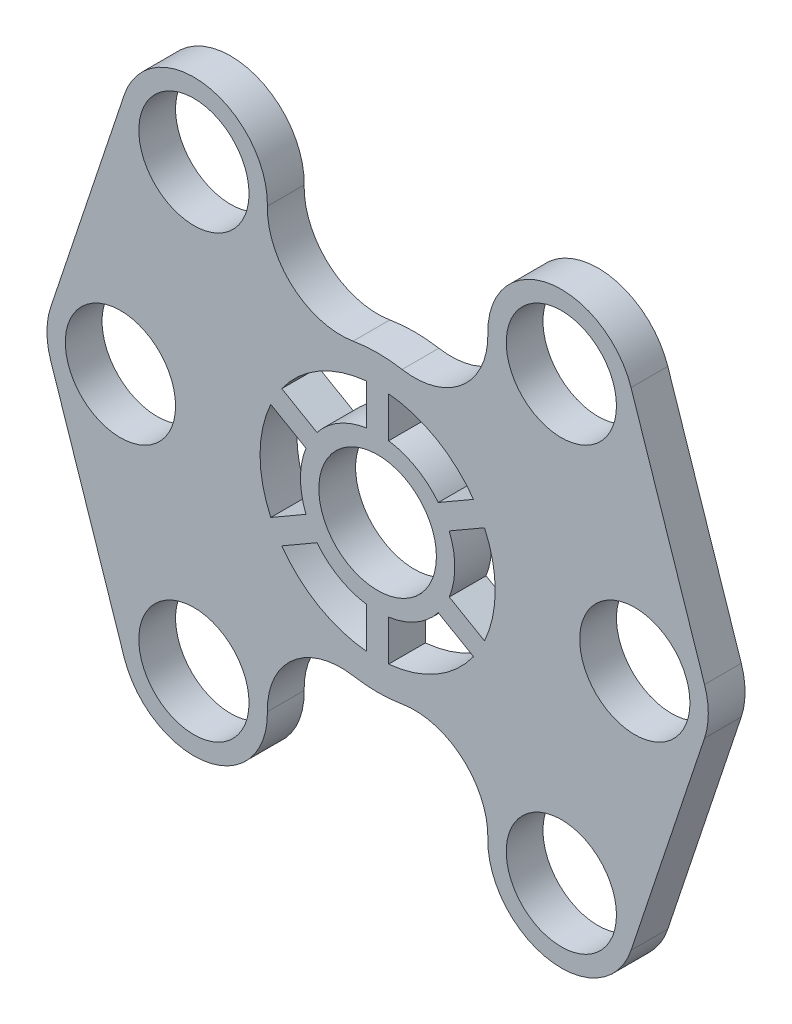
SolidWorks part; units mm, degrees
ref_plane "Front Plane" through (0, 0, 0) normal (0, 0, 1) x (1, 0, 0)
ref_plane "Top Plane" through (0, 0, 0) normal (0, 1, 0) x (1, 0, 0)
ref_plane "Right Plane" through (0, 0, 0) normal (1, 0, 0) x (0, 0, -1)
sketch "Sketch1" plane through (0, 0, 0) normal (0, 0, 1) x (1, 0, 0)
  line L0 (0, -30.4712) -> (0, 30.4712) construction
  line L1 (0, 0) -> (51.2653, 0) construction
  line L2 (-3, -20.7846) -> (-3, -31.8591)
  line L3 (3, -20.7846) -> (3, -31.8591)
  line L4 (-19.5, -7.7942) -> (-29.0908, -13.3315)
  line L5 (-16.5, -12.9904) -> (-26.0908, -18.5276)
  line L6 (-16.5, 12.9904) -> (-26.0908, 18.5276)
  line L7 (-19.5, 7.7942) -> (-29.0908, 13.3315)
  line L8 (3, 20.7846) -> (3, 31.8591)
  line L9 (-3, 20.7846) -> (-3, 31.8591)
  line L10 (19.5, 7.7942) -> (29.0908, 13.3315)
  line L11 (16.5, 12.9904) -> (26.0908, 18.5276)
  line L12 (16.5, -12.9904) -> (26.0908, -18.5276)
  line L13 (19.5, -7.7942) -> (29.0908, -13.3315)
  line L14 (68.9737, 66.3246) -> (88.9737, 6.3246)
  line L15 (68.9737, -66.3246) -> (88.9737, -6.3246)
  line L16 (0, 0) -> (-51.2653, 0) construction
  line L17 (-68.9737, -66.3246) -> (-88.9737, -6.3246)
  line L18 (-68.9737, 66.3246) -> (-88.9737, 6.3246)
  circle A0 centre (0, 0) radius 40
  arc A1 (-3, 31.8591) -> (-26.0908, 18.5276) centre (0, 0) ccw
  arc A2 (-3, 20.7846) -> (-16.5, 12.9904) centre (0, 0) ccw
  circle A3 centre (0, 0) radius 16
  arc A4 (26.0908, 18.5276) -> (3, 31.8591) centre (0, 0) ccw
  arc A5 (16.5, 12.9904) -> (3, 20.7846) centre (0, 0) ccw
  arc A6 (29.0908, -13.3315) -> (29.0908, 13.3315) centre (0, 0) ccw
  arc A7 (19.5, -7.7942) -> (19.5, 7.7942) centre (0, 0) ccw
  arc A8 (3, -31.8591) -> (26.0908, -18.5276) centre (0, 0) ccw
  arc A9 (3, -20.7846) -> (16.5, -12.9904) centre (0, 0) ccw
  arc A10 (-26.0908, -18.5276) -> (0, -32) centre (0, 0) ccw
  arc A11 (-16.5, -12.9904) -> (0, -21) centre (0, 0) ccw
  arc A12 (-29.0908, 13.3315) -> (-29.0908, -13.3315) centre (0, 0) ccw
  arc A13 (-19.5, 7.7942) -> (-19.5, -7.7942) centre (0, 0) ccw
  circle A14 centre (50, 60) radius 15
  arc A15 (68.9737, 66.3246) -> (30.0044, 59.5797) centre (50, 60) ccw
  arc A16 (68.9737, -66.3246) -> (30.0044, -59.5797) centre (50, -60) cw
  circle A17 centre (50, -60) radius 15
  circle A18 centre (70, 0) radius 20
  circle A19 centre (70, 0) radius 15
  arc A20 (6.6726, 39.4395) -> (30.0044, 59.5797) centre (10.0088, 59.1593) ccw
  arc A21 (6.6726, -39.4395) -> (30.0044, -59.5797) centre (10.0088, -59.1593) cw
  arc A22 (-6.6726, -39.4395) -> (-30.0044, -59.5797) centre (-10.0088, -59.1593) ccw
  arc A23 (-6.6726, 39.4395) -> (-30.0044, 59.5797) centre (-10.0088, 59.1593) cw
  circle A24 centre (-70, 0) radius 15
  circle A25 centre (-70, 0) radius 20
  circle A26 centre (-50, -60) radius 15
  arc A27 (-68.9737, -66.3246) -> (-30.0044, -59.5797) centre (-50, -60) ccw
  arc A28 (-68.9737, 66.3246) -> (-30.0044, 59.5797) centre (-50, 60) cw
  circle A29 centre (-50, 60) radius 15
  point P14 (0, 0)
  point P37 (0, 0)
  dimension "D1" = 32
  dimension "D2" = 42
  dimension "D3" = 64
  dimension "D4" = 80
  dimension "D9" = 30
  dimension "D10" = 40
  dimension "D11" = 40
  dimension "D12" = 30
  dimension "D14" = 20
  dimension "D5" = 6
  dimension "D7" = 50
  dimension "D8" = 60
  dimension "D13" = 20
  dimension "D6" = 6
extrude "Boss-Extrude1" add sketch "Sketch1" along normal blind 10 contours A0 A21 A16 L15 A18 L14 A15 A20 A17 A14 | A28 L18 A25 L17 A27 A22 A0 A23 A26 A29 | A25 A24 | A18 A19 | A3 | A5 L11 A4 L8 | A7 L13 A6 L10 | A9 L3 A8 L12 | A11 L5 A10 L2 | A13 L7 A12 L4 | A2 L9 A1 L6
